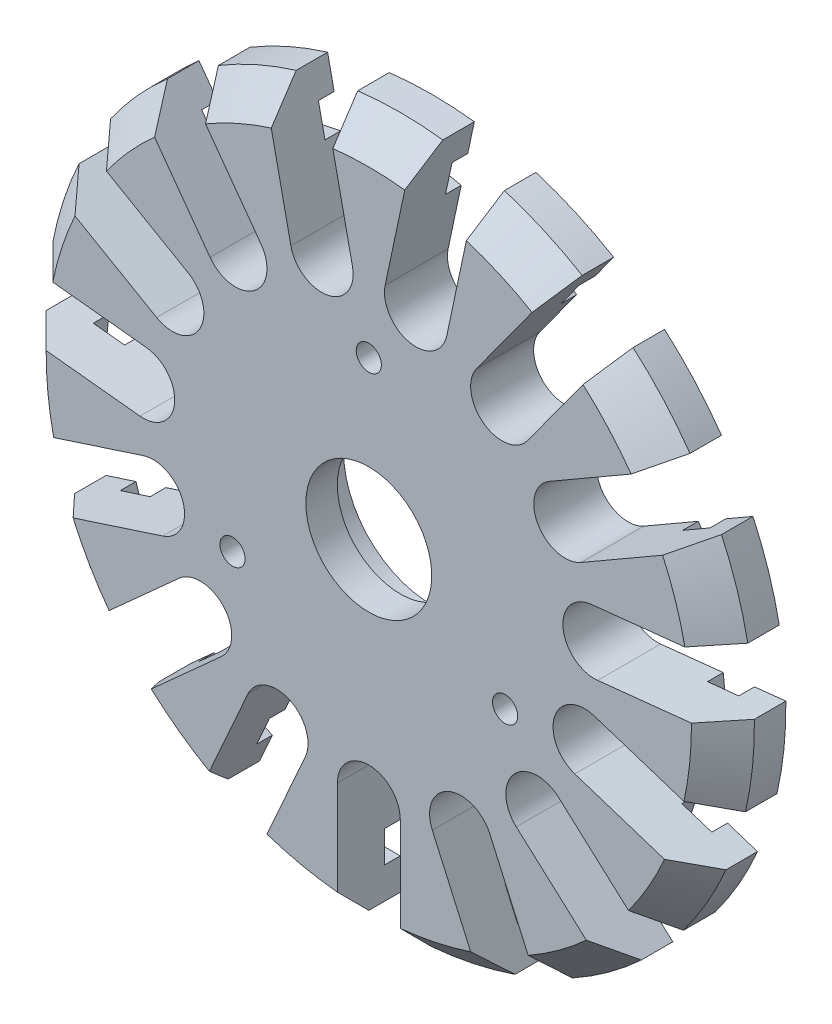
SolidWorks part; units mm, degrees
material "Liga 1060"
ref_plane "Plano frontal" through (0, 0, 0) normal (0, 0, 1) x (1, 0, 0)
ref_plane "Plano superior" through (0, 0, 0) normal (0, 1, 0) x (1, 0, 0)
ref_plane "Plano direito" through (0, 0, 0) normal (1, 0, 0) x (0, 0, -1)
sketch "Esboço1" plane through (0, 0, 0) normal (0, 0, 1) x (1, 0, 0)
  circle A0 centre (0, 0) radius 22.5
  dimension "D1" = 45
extrude "Ressalto-extrusão1" add sketch "Esboço1" along normal blind 4
chamfer "Chanfro1" distance 2 angle 45 1 edges at (22.5, 0, 4)
sketch "Esboço2" plane through (0, 0, 0) normal (0, 0, -1) x (-1, 0, 0)
  line L0 (0, 0) -> (0, 14.4289) construction
  line L1 (2, -22.4109) -> (2, -14.4109)
  line L2 (-2, -22.4109) -> (-2, -14.4109)
  arc A0 (-2, -22.4109) -> (2, -22.4109) centre (0, 0) ccw
  circle A1 centre (0, 0) radius 22.5 construction
  arc A2 (2, -14.4109) -> (-2, -14.4109) centre (0, -14.4109) ccw
  dimension "D1" = 4
  dimension "D2" = 8
extrude "Corte-extrusão1" cut sketch "Esboço2" against normal through all
sketch "Esboço3" plane through (0, 0, 0) normal (0, 0, -1) x (-1, 0, 0)
  circle A0 centre (0, 0) radius 4
  dimension "D1" = 8
extrude "Corte-extrusão2" cut sketch "Esboço3" against normal through all
sketch "Esboço4" plane through (0, 0, 0) normal (0, 0, -1) x (-1, 0, 0)
  circle A0 centre (0, 0) radius 5.6
  dimension "D1" = 11.2
extrude "Corte-extrusão3" cut sketch "Esboço4" against normal blind 2
pattern_circular "PadrãoCircular1" count 15 over 360 about axis through (0, 0, 0) along (0, 0, 1) of "Corte-extrusão1"
sketch "Esboço5" plane through (0, 0, 0) normal (0, 0, -1) x (-1, 0, 0)
  circle A0 centre (0, 0) radius 18.5
  circle A1 centre (0, 0) radius 20.5
  dimension "D1" = 41
  dimension "D2" = 37
sketch "Esboço9" plane through (0, 0, 0) normal (0, 0, -1) x (-1, 0, 0)
  line L0 (0, 0) -> (0, 6) construction
  dimension "D1" = 6
sketch "Esboço11" plane through (0, 0, 0) normal (0, 0, -1) x (-1, 0, 0)
  line L0 (0, 0) -> (0, -22.5) construction
  line L1 (2, -22.4109) -> (2, -20.4109) construction
  line L2 (2, -22.4109) -> (2, -14.4109) construction
  line L3 (3.5, -20.4109) -> (-3.5, -20.4109)
  line L4 (-3.5, -20.4109) -> (-3.5, -18.4109)
  line L5 (-3.5, -18.4109) -> (3.5, -18.4109)
  line L6 (3.5, -18.4109) -> (3.5, -20.4109)
  arc A2 (-7.2883, -21.2869) -> (-2, -22.4109) centre (0, 0) ccw construction
  point P13 (0, -20.4109)
  dimension "D1" = 7
  dimension "D2" = 2
  dimension "D3" = 2
extrude "Corte-extrusão4" cut sketch "Esboço11" against normal blind 1
pattern_circular "PadrãoCircular3" count 15 over 360 about axis through (0, 0, 0) along (0, 0, 1) of "Corte-extrusão4"
sketch "Esboço12" plane through (0, 0, 0) normal (0, 0, -1) x (-1, 0, 0)
  circle A0 centre (0, 0) radius 10
  point P3 (0, 10)
  dimension "D1" = 20
hole_wizard "Broca de rosquear para tarraxa de M21" positions "3DSketch2" profile "Esboço14" hole size "M2" standard "ISO" end condition through all
sketch3d "3DSketch2"
  point P0 (0, 10, 0)
sketch "Esboço14" plane through (0, 10, 0) normal (1, 0, 0) x (0, 1, 0)
  line L0 (0, 0) -> (0, 4)
  line L1 (0, 4) -> (0.8, 4)
  line L2 (0.8, 4) -> (0.8, 0)
  line L5 (0.8, 0) -> (0, 0)
  line L11 (0, -6.35) -> (0, 107.95) construction
  dimension "Thru Hole Dia." = 1.6
  dimension "Thru Hole Depth" = 4
pattern_circular "PadrãoCircular4" count 3 over 360 about axis through (0, 0, 0) along (0, 0, 1) of "Broca de rosquear para tarraxa de M21"
